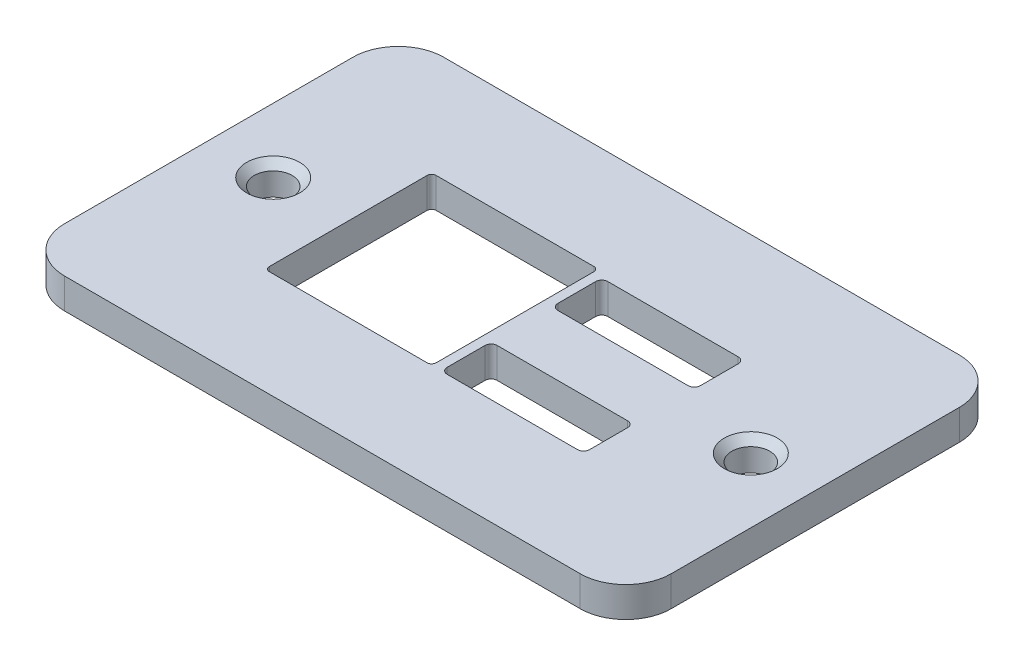
SolidWorks part; units mm, degrees
ref_plane "前视基准面" through (0, 0, 0) normal (0, 0, 1) x (1, 0, 0)
ref_plane "上视基准面" through (0, 0, 0) normal (0, 1, 0) x (1, 0, 0)
ref_plane "右视基准面" through (0, 0, 0) normal (1, 0, 0) x (0, 0, -1)
sketch "草图1" plane through (0, 0, 0) normal (0, 1, 0) x (1, 0, 0)
  line L1 (-17, 12.5) -> (17, 12.5)
  line L2 (-20, 9.5) -> (-20, -9.5)
  line L3 (-17, -12.5) -> (17, -12.5)
  line L4 (20, 9.5) -> (20, -9.5)
  line L5 (-20, 12.5) -> (20, -12.5) construction
  line L6 (-20, -12.5) -> (20, 12.5) construction
  arc A0 (-20, 9.5) -> (-17, 12.5) centre (-17, 9.5) cw
  arc A1 (20, 9.5) -> (17, 12.5) centre (17, 9.5) ccw
  arc A2 (20, -9.5) -> (17, -12.5) centre (17, -9.5) cw
  arc A3 (-17, -12.5) -> (-20, -9.5) centre (-17, -9.5) cw
  point P0 (0, 0)
  dimension "D3" = 3
  dimension "D4" = 3
  dimension "D1" = 40
  dimension "D2" = 25
extrude "凸台-拉伸1" add sketch "草图1" along normal blind 2
sketch "草图2" plane through (0, 2, 0) normal (0, 1, 0) x (1, 0, 0)
  line L0 (-22.5674, 0) -> (23.6783, 0) construction
  circle A0 centre (-15.75, 0) radius 1.25
  dimension "D2" = 2.5
  dimension "D1" = 15.75
extrude "切除-拉伸1" cut sketch "草图2" against normal up to next contours A0
chamfer "倒角1" distance 0.5 angle 45 1 edges at (-15.75, 2, 1.25)
mirror "镜向3" about plane through (0, 0, 0) normal (1, 0, 0) of "倒角1", "切除-拉伸1"
sketch "草图3" plane through (0, 2, 0) normal (0, 1, 0) x (1, 0, 0)
  line L0 (-20, 9.5) -> (-20, -9.5) construction
  line L1 (-10.5, 5.5) -> (-0.1, 5.5)
  line L2 (-10.8, 5.2) -> (-10.8, -5.2)
  line L3 (-10.5, -5.5) -> (-0.1, -5.5)
  line L4 (0.2, 5.2) -> (0.2, -5.2)
  line L5 (-10.8, 5.5) -> (0.2, -5.5) construction
  line L6 (-10.8, -5.5) -> (0.2, 5.5) construction
  line L7 (-17, -12.5) -> (17, -12.5) construction
  arc A0 (-10.8, -5.2) -> (-10.5, -5.5) centre (-10.5, -5.2) ccw
  arc A1 (0.2, -5.2) -> (-0.1, -5.5) centre (-0.1, -5.2) cw
  arc A2 (0.2, 5.2) -> (-0.1, 5.5) centre (-0.1, 5.2) ccw
  arc A3 (-10.8, 5.2) -> (-10.5, 5.5) centre (-10.5, 5.2) cw
  point P0 (-5.3, 0)
  dimension "D5" = 0.3
  dimension "D1" = 14.7
  dimension "D2" = 11
  dimension "D3" = 11
  dimension "D4" = 7
extrude "切除-拉伸2" cut sketch "草图3" against normal up to next
sketch "草图4" plane through (0, 2, 0) normal (0, 1, 0) x (1, 0, 0)
  line L0 (20, -9.5) -> (20, 9.5) construction
  line L1 (1.22, -2.2) -> (9.82, -2.2)
  line L2 (0.82, -2.6) -> (0.82, -5.1)
  line L3 (1.22, -5.5) -> (9.82, -5.5)
  line L4 (10.22, -2.6) -> (10.22, -5.1)
  line L5 (0.82, -2.2) -> (10.22, -5.5) construction
  line L6 (0.82, -5.5) -> (10.22, -2.2) construction
  line L7 (-10.5, -5.5) -> (-0.1, -5.5) construction
  arc A0 (9.82, -2.2) -> (10.22, -2.6) centre (9.82, -2.6) cw
  arc A1 (9.82, -5.5) -> (10.22, -5.1) centre (9.82, -5.1) ccw
  arc A2 (1.22, -5.5) -> (0.82, -5.1) centre (1.22, -5.1) cw
  arc A3 (0.82, -2.6) -> (1.22, -2.2) centre (1.22, -2.6) cw
  point P0 (5.52, -3.85)
  dimension "D4" = 0.4
  dimension "D1" = 14.48
  dimension "D2" = 9.4
  dimension "D3" = 3.3
extrude "切除-拉伸3" cut sketch "草图4" against normal up to next
sketch "草图5" plane through (0, 2, 0) normal (0, 1, 0) x (1, 0, 0)
  line L0 (0.82, -2.6) -> (0.82, -5.1) construction
  line L1 (1.22, 5.1) -> (9.82, 5.1)
  line L2 (0.82, 4.7) -> (0.82, 2.2)
  line L3 (1.22, 1.8) -> (9.82, 1.8)
  line L4 (10.22, 4.7) -> (10.22, 2.2)
  line L5 (0.82, 5.1) -> (10.22, 1.8) construction
  line L6 (0.82, 1.8) -> (10.22, 5.1) construction
  line L7 (10.22, -5.1) -> (10.22, -2.6) construction
  line L8 (17, 12.5) -> (-17, 12.5) construction
  arc A0 (9.82, 5.1) -> (10.22, 4.7) centre (9.82, 4.7) cw
  arc A1 (9.82, 1.8) -> (10.22, 2.2) centre (9.82, 2.2) ccw
  arc A2 (0.82, 2.2) -> (1.22, 1.8) centre (1.22, 2.2) ccw
  arc A3 (0.82, 4.7) -> (1.22, 5.1) centre (1.22, 4.7) cw
  point P0 (5.52, 3.45)
  dimension "D2" = 0.4
  dimension "D1" = 3.3
  dimension "D3" = 7.4
extrude "切除-拉伸4" cut sketch "草图5" against normal up to next contours L1 A0 L4 A1 L3 A2 L2 A3
